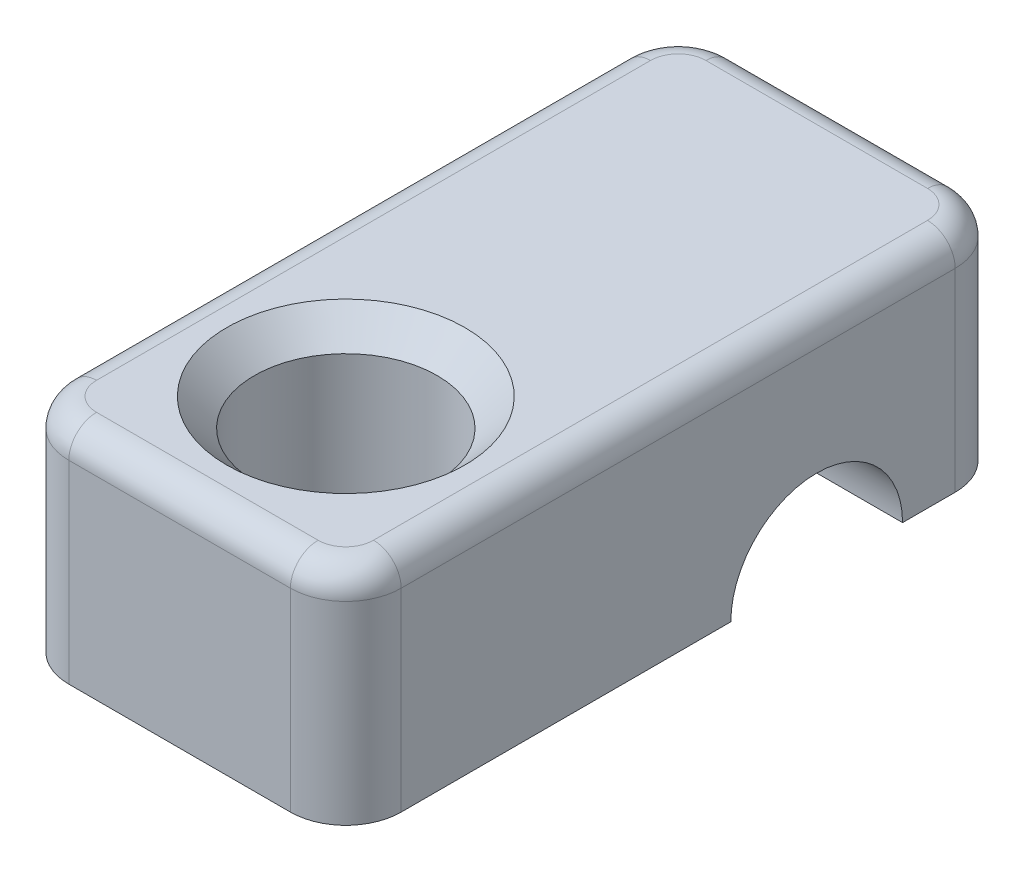
SolidWorks part; units mm, degrees
ref_plane "前基準面" through (0, 0, 0) normal (0, 0, 1) x (1, 0, 0)
ref_plane "上基準面" through (0, 0, 0) normal (0, 1, 0) x (1, 0, 0)
ref_plane "右基準面" through (0, 0, 0) normal (1, 0, 0) x (0, 0, -1)
sketch "草圖1" plane through (0, 0, 0) normal (1, 0, 0) x (0, 0, -1)
  line L0 (0, 0) -> (6.95, 0)
  line L1 (0, 0) -> (0, 4)
  line L2 (0, 4) -> (12, 4)
  line L3 (12, 4) -> (12, 0)
  line L4 (10.05, 0) -> (12, 0)
  arc A0 (10.05, 0) -> (6.95, 0) centre (8.5, 0) ccw
  dimension "D3" = 3.1
  dimension "D1" = 4
  dimension "D2" = 12
  dimension "D4" = 3.5
extrude "填料-伸長1" add sketch "草圖1" along normal blind 6
sketch "草圖2" plane through (0, 0, 0) normal (0, -1, 0) x (-1, 0, 0)
  line L0 (-3, 0) -> (-3, 6.95) construction
  line L1 (-6, 0) -> (0, 0) construction
  line L2 (-6, 6.95) -> (0, 6.95) construction
  circle A0 centre (-3, 3) radius 1.65
  dimension "D1" = 3.3
  dimension "D2" = 3
extrude "除料-伸長1" cut sketch "草圖2" against normal blind 6
fillet "圓角1" radius 1 4 edges at (6, 2, -12) (0, 2, -12) (6, 2, 0) (0, 2, 0)
chamfer "導角1" distance 0.5 angle 45 1 edges at (3, 4, -4.65)
fillet "圓角2" radius 0.5 8 edges at (0.2929, 4, -11.7071) (3, 4, -12) (5.7071, 4, -11.7071) (6, 4, -6) (5.7071, 4, -0.2929) (3, 4, 0) (0.2929, 4, -0.2929) (0, 4, -6)
